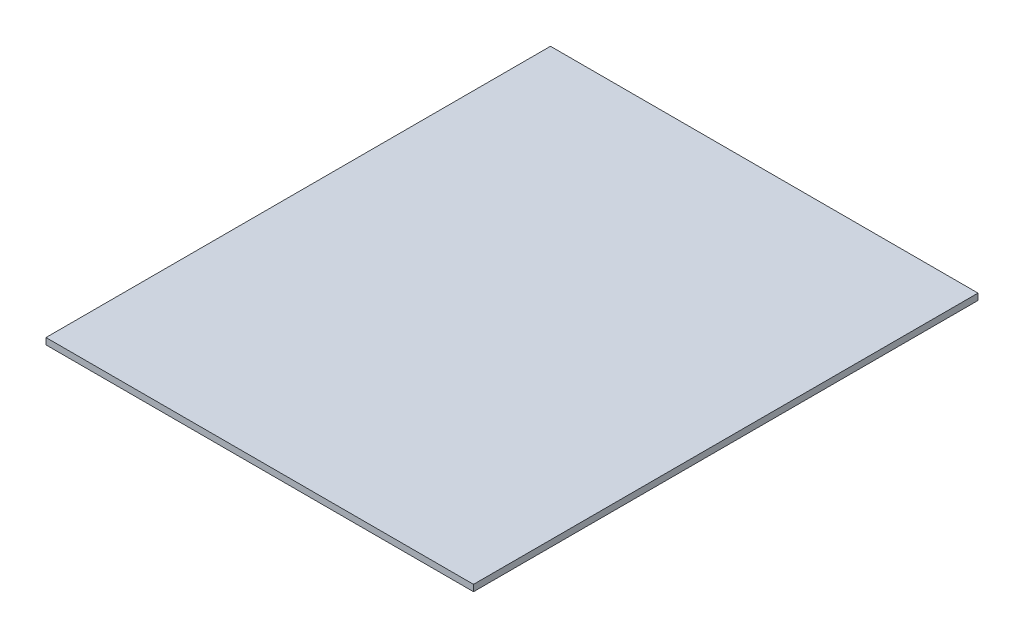
SolidWorks part; units mm, degrees
ref_plane "Front Plane" through (0, 0, 0) normal (0, 0, 1) x (1, 0, 0)
ref_plane "Top Plane" through (0, 0, 0) normal (0, 1, 0) x (1, 0, 0)
ref_plane "Right Plane" through (0, 0, 0) normal (1, 0, 0) x (0, 0, -1)
sketch "Sketch1" plane through (0, 0, 0) normal (0, 1, 0) x (1, 0, 0)
  line L1 (0, 0) -> (200, 0)
  line L2 (0, 0) -> (0, -236)
  line L3 (0, -236) -> (200, -236)
  line L4 (200, 0) -> (200, -236)
  dimension "D1" = 236
  dimension "D2" = 200
extrude "Boss-Extrude1" add sketch "Sketch1" along normal blind 3
